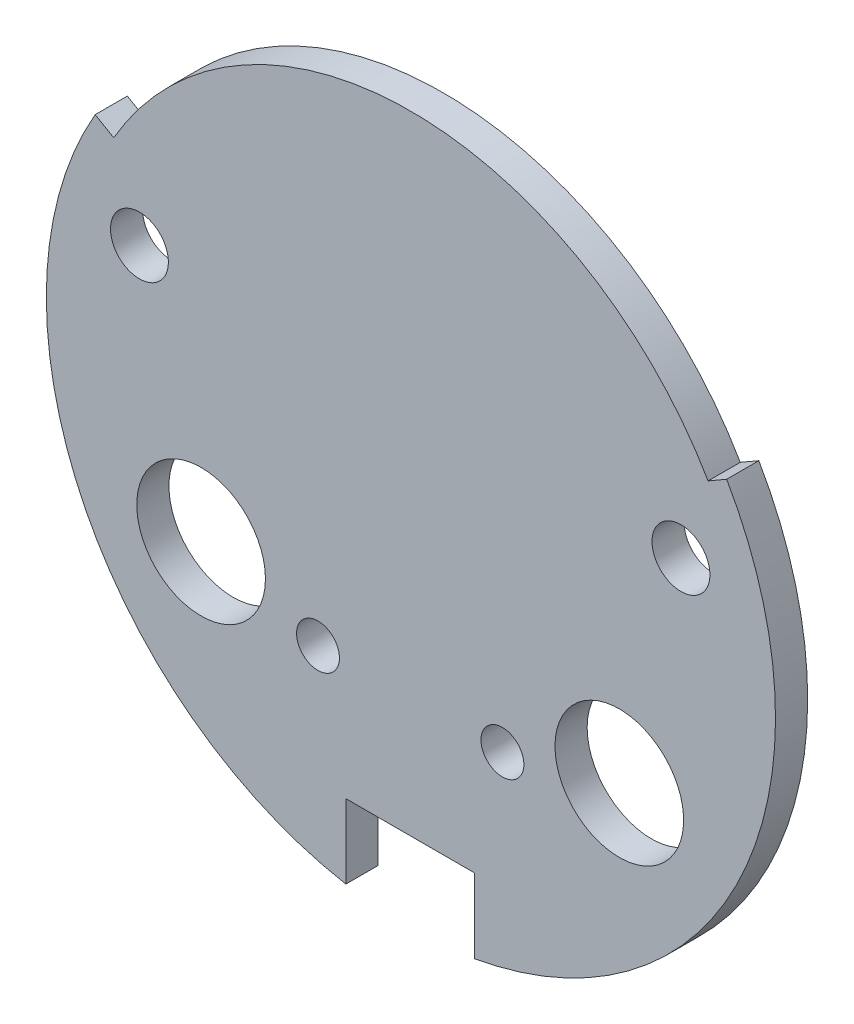
SolidWorks part; units mm, degrees
ref_plane "Front Plane" through (0, 0, 0) normal (0, 0, 1) x (1, 0, 0)
ref_plane "Top Plane" through (0, 0, 0) normal (0, 1, 0) x (1, 0, 0)
ref_plane "Right Plane" through (0, 0, 0) normal (1, 0, 0) x (0, 0, -1)
sketch "Sketch1" plane through (0, 0, 0) normal (0, 0, 1) x (1, 0, 0)
  line L0 (-3.3523, -12.4645) -> (2.6477, -12.4645)
  line L1 (-3.3523, -12.4645) -> (-3.3523, -15.9167)
  line L2 (2.6477, -12.4645) -> (2.6477, -15.9287)
  line L3 (-14.1754, 8.8105) -> (-15.0415, 9.3105)
  line L7 (14.4034, 9.3105) -> (13.5374, 8.8105)
  arc A1 (13.5374, 8.8105) -> (-14.1754, 8.8105) centre (-0.319, 0.8105) ccw
  arc A2 (-15.0415, 9.3105) -> (-3.3523, -15.9167) centre (-0.319, 0.8105) ccw
  arc A3 (2.6477, -15.9287) -> (14.4034, 9.3105) centre (-0.319, 0.8105) ccw
  point P3 (-0.3523, -12.4645)
  dimension "D1" = 17
  dimension "D2" = 16
  dimension "D3" = 1
  dimension "D4" = 1
  dimension "D5" = 6
  dimension "D6" = 13.275
extrude "Boss-Extrude1" add sketch "Sketch1" along normal blind 1.5
sketch "Sketch2" plane through (0, 0, 1.5) normal (0, 0, 1) x (1, 0, 0)
  line L0 (-23.4253, -5.4645) -> (23.8274, -5.4645) construction
  line L1 (-3.3523, -12.4645) -> (2.6477, -12.4645) construction
  line L2 (-0.3523, -12.4645) -> (-0.3523, 9.3801) construction
  circle A0 centre (-10.1023, -5.4645) radius 3
  circle A1 centre (9.3977, -5.4645) radius 3
  circle A2 centre (-12.9773, 5.0605) radius 1.35
  circle A3 centre (12.2727, 5.0605) radius 1.35
  circle A4 centre (-4.6523, -6.9395) radius 1
  circle A5 centre (3.9477, -6.9395) radius 1
  dimension "D2" = 6
  dimension "D3" = 9.75
  dimension "D4" = 2.7
  dimension "D5" = 10.525
  dimension "D6" = 12.625
  dimension "D7" = 1.475
  dimension "D8" = 2
  dimension "D9" = 4.3
  dimension "D1" = 7
extrude "Cut-Extrude1" cut sketch "Sketch2" against normal through all
